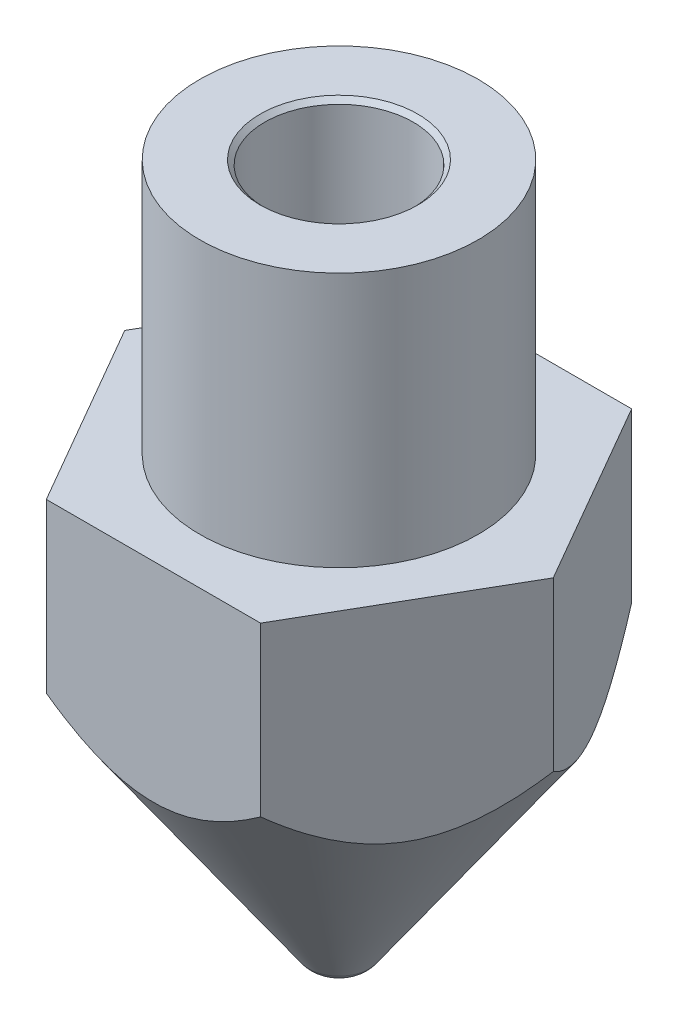
SolidWorks part; units mm, degrees
material "latón"
ref_plane "Alzado" through (0, 0, 0) normal (0, 0, 1) x (1, 0, 0)
ref_plane "Planta" through (0, 0, 0) normal (0, 1, 0) x (1, 0, 0)
ref_plane "Vista lateral" through (0, 0, 0) normal (1, 0, 0) x (0, 0, -1)
sketch "Croquis1" plane through (0, 0, 0) normal (0, 0, 1) x (1, 0, 0)
  line L0 (0, 0) -> (0, 177.6793) construction
  line L1 (0, 0) -> (0.2, 0) construction
  line L2 (0.2, 0) -> (0.2, 1.2)
  line L3 (0.2, 1.2) -> (1.6, 3.1994)
  line L4 (1.6, 3.1994) -> (1.6, 15)
  line L6 (3, 15) -> (3, 9.5)
  line L7 (3.6509, 4.5) -> (3.6509, 9.5)
  line L8 (3.6509, 4.5) -> (0.5, 0)
  line L9 (0.5, 0) -> (0.2, 0)
  line L10 (3.6509, 9.5) -> (3, 9.5)
  line L11 (1.6, 15) -> (3, 15)
  dimension "D1" = 0.2
  dimension "D2" = 35
  dimension "D3" = 1.2
  dimension "D4" = 0.5
  dimension "D5" = 3
  dimension "D6" = 1.6
  dimension "D8" = 4.5
  dimension "D9" = 5.5
  dimension "D11" = 15
revolve "Revolución1" add sketch "Croquis1" angle 360 about L0
cosmetic thread "Rosca cosmética1" parameters "D2"=4.891
sketch "Croquis3" plane through (0, 9.5, 0) normal (0, 1, 0) x (1, 0, 0)
  line L0 (-2.3094, -4) -> (2.3094, -4)
  line L1 (2.3094, -4) -> (4.6188, 0)
  line L3 (4.6188, 0) -> (2.3094, 4)
  line L4 (2.3094, 4) -> (-2.3094, 4)
  line L5 (-2.3094, 4) -> (-4.6188, 0)
  line L6 (-4.6188, 0) -> (-2.3094, -4)
  circle A0 centre (0, 0) radius 4 construction
  circle A1 centre (0, 0) radius 3.6509
  circle A2 centre (0, 0) radius 3.6509 construction
  dimension "D1" = 8
extrude "Saliente-Extruir1" add sketch "Croquis3" against normal blind 5
fillet "Redondeo1" radius 0.5 1 edges at (0, 0, -0.5)
chamfer "Chaflán1" distance 0.1 angle 45 1 edges at (0, 15, -1.6)
sketch "Croquis5" plane through (0, 0, 0) normal (0, 0, 1) x (1, 0, 0)
  line L0 (3.6509, 4.5) -> (4.6188, 5.8823)
  line L1 (4.6188, 4.5) -> (4.6188, 9.5) construction
  line L2 (4.6188, 5.8823) -> (4.6188, 4.5)
  line L3 (4.6188, 4.5) -> (3.6509, 4.5)
  line L4 (0.6493, 0.2132) -> (3.6509, 4.5) construction
  line L5 (0, 15) -> (0, 0) construction
  line L6 (1.7, 15) -> (-1.7, 15) construction
revolve "Cortar-Revolución1" cut sketch "Croquis5" angle 360 about L5
